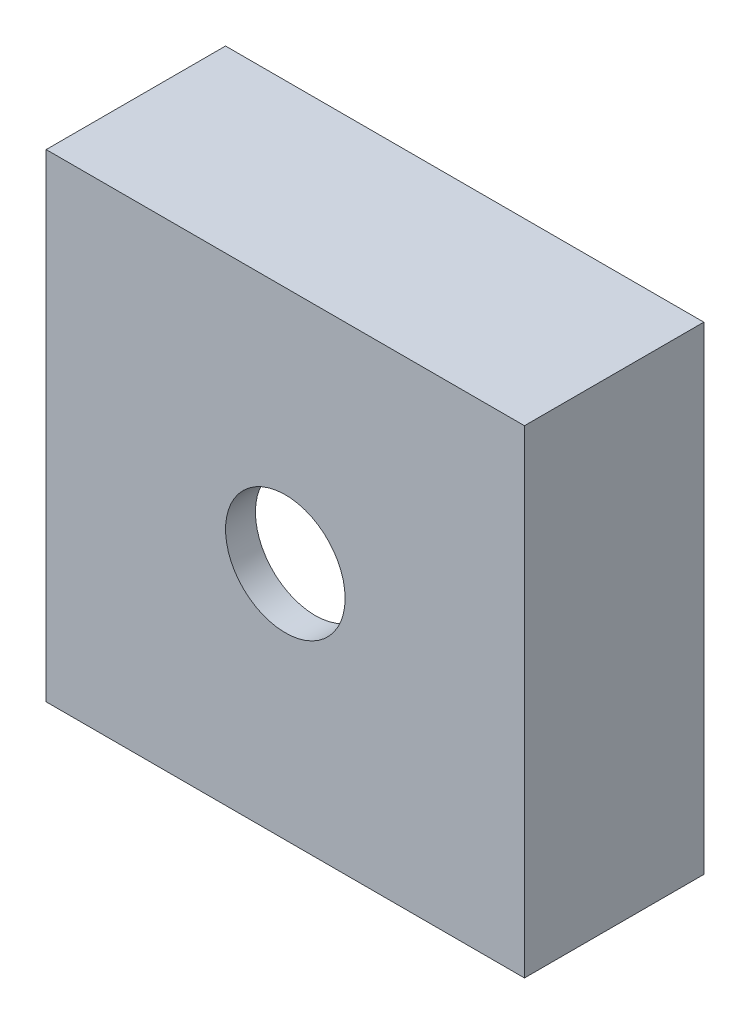
SolidWorks part; units mm, degrees
ref_plane "Front Plane" through (0, 0, 0) normal (0, 0, 1) x (1, 0, 0)
ref_plane "Top Plane" through (0, 0, 0) normal (0, 1, 0) x (1, 0, 0)
ref_plane "Right Plane" through (0, 0, 0) normal (1, 0, 0) x (0, 0, -1)
sketch "Sketch1" plane through (0, 0, 0) normal (0, 0, 1) x (1, 0, 0)
  line L1 (-40, -40) -> (40, -40)
  line L2 (-40, -40) -> (-40, 40)
  line L3 (-40, 40) -> (40, 40)
  line L4 (40, -40) -> (40, 40)
  line L5 (-40, -40) -> (40, 40) construction
  line L6 (-40, 40) -> (40, -40) construction
  point P0 (0, 0)
  dimension "D1" = 80
  dimension "D2" = 80
extrude "Boss-Extrude1" add sketch "Sketch1" along normal blind 30
shell "Shell1" thickness 5
sketch "Sketch2" plane through (0, 0, 30) normal (0, 0, 1) x (1, 0, 0)
  line L1 (-15, -6.5) -> (15, -6.5)
  line L2 (-15, -6.5) -> (-15, 6.5)
  line L3 (-15, 6.5) -> (15, 6.5)
  line L4 (15, -6.5) -> (15, 6.5)
  line L5 (-15, -6.5) -> (15, 6.5) construction
  line L6 (-15, 6.5) -> (15, -6.5) construction
  point P0 (0, 0)
  dimension "D1" = 30
  dimension "D2" = 13
sketch "Sketch3" plane through (0, 0, 30) normal (0, 0, 1) x (1, 0, 0)
  circle A0 centre (0, 0) radius 10
  dimension "D1" = 20
extrude "Cut-Extrude1" cut sketch "Sketch3" against normal blind 10
